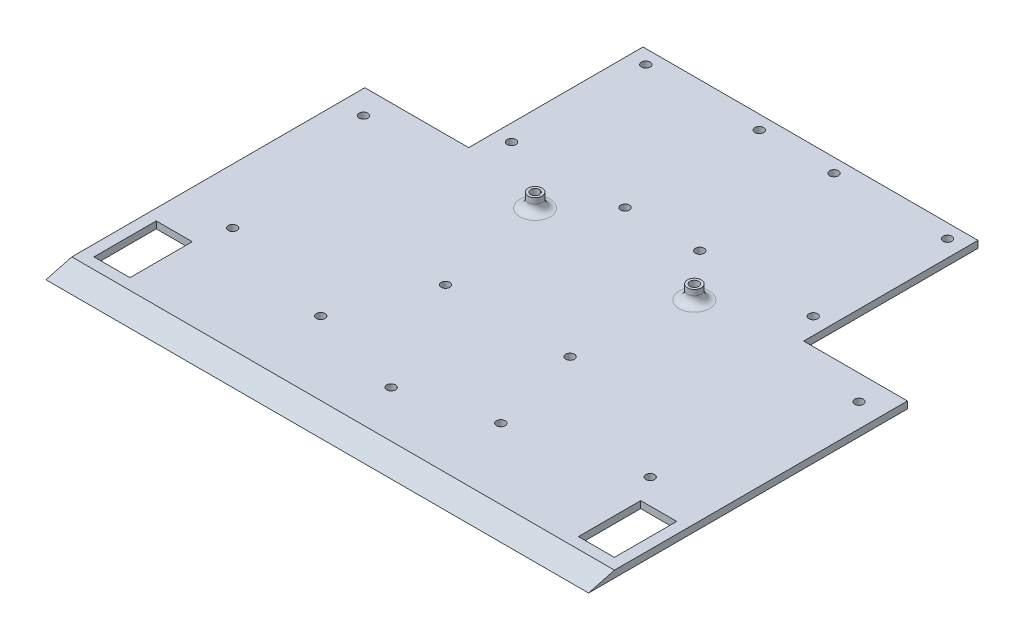
SolidWorks part; units mm, degrees
ref_plane "Alzado" through (0, 0, 0) normal (0, 0, 1) x (1, 0, 0)
ref_plane "Planta" through (0, 0, 0) normal (0, 1, 0) x (1, 0, 0)
ref_plane "Vista lateral" through (0, 0, 0) normal (1, 0, 0) x (0, 0, -1)
sketch "Croquis1" plane through (0, 0, 0) normal (1, 0, 0) x (0, 0, -1)
  line L0 (0, 0) -> (178.17, 0)
  line L1 (178.17, 0) -> (178.17, 2.5)
  line L2 (178.17, 2.5) -> (9.3301, 2.5)
  line L3 (0, 0) -> (9.3301, 2.5)
  dimension "D1" = 178.17
  dimension "D2" = 2.5
  dimension "D3" = 165
extrude "Saliente-Extruir1" add sketch "Croquis1" along normal blind 196
sketch "Croquis2" plane through (0, 0, 0) normal (0, -1, 0) x (-1, 0, 0)
  line L1 (-37.5, 115.1801) -> (0, 115.1801)
  line L2 (-37.5, 115.1801) -> (-37.5, 178.17)
  line L3 (-37.5, 178.17) -> (0, 178.17)
  line L4 (0, 115.1801) -> (0, 178.17)
  line L5 (-37.5, 115.1801) -> (0, 178.17) construction
  line L6 (-37.5, 178.17) -> (0, 115.1801) construction
  line L7 (-158.5, 115.1801) -> (-196, 115.1801)
  line L8 (-158.5, 115.1801) -> (-158.5, 178.17)
  line L9 (-158.5, 178.17) -> (-196, 178.17)
  line L10 (-196, 115.1801) -> (-196, 178.17)
  line L11 (-158.5, 115.1801) -> (-196, 178.17) construction
  line L12 (-158.5, 178.17) -> (-196, 115.1801) construction
  point P4 (-18.75, 146.6751)
  point P11 (-177.25, 146.6751)
extrude "Cortar-Extruir1" cut sketch "Croquis2" against normal up to next
sketch "Croquis4" plane through (0, 2.5, 0) normal (0, 1, 0) x (1, 0, 0)
  line L7 (4, 13.3301) -> (17, 13.3301)
  line L8 (4, 13.3301) -> (4, 35.8301)
  line L9 (4, 35.8301) -> (17, 35.8301)
  line L10 (17, 13.3301) -> (17, 35.8301)
  line L11 (4, 13.3301) -> (17, 35.8301) construction
  line L12 (4, 35.8301) -> (17, 13.3301) construction
  point P9 (10.5, 24.5801)
  dimension "D3" = 22.5
  dimension "D4" = 13
extrude "Cortar-Extruir2" cut sketch "Croquis4" against normal up to next
ref_plane "Plano1" through (98, 0, 0) normal (1, 0, 0) x (0, 0, -1)
mirror "Simetría1" about plane through (98, 0, 0) normal (1, 0, 0) of "Cortar-Extruir2"
sketch "Sketch1" plane through (0, 2.5, 0) normal (0, 1, 0) x (1, 0, 0)
  circle A0 centre (187.5, 106.1801) radius 1.585
  circle A1 centre (8.5, 106.1801) radius 1.585
extrude "Cut-Extrude1" cut sketch "Sketch1" against normal up to next
sketch "Sketch2" plane through (0, 2.5, 0) normal (0, 1, 0) x (1, 0, 0)
  circle A0 centre (98.5, 26.1801) radius 1.585
extrude "Cut-Extrude2" cut sketch "Sketch2" against normal up to next
sketch "Sketch3" plane through (0, 2.5, 0) normal (0, 1, 0) x (1, 0, 0)
  circle A0 centre (111.5, 124.67) radius 1.585
  circle A1 centre (152.5, 124.67) radius 1.585
  circle A2 centre (152.5, 173.17) radius 1.585
  circle A3 centre (111.5, 173.17) radius 1.585
  circle A4 centre (84.5, 173.17) radius 1.585
  circle A5 centre (43.5, 173.17) radius 1.585
  circle A6 centre (43.5, 124.67) radius 1.585
  circle A7 centre (84.5, 124.67) radius 1.585
extrude "Cut-Extrude3" cut sketch "Sketch3" against normal up to next
sketch "Sketch4" plane through (0, 2.5, 0) normal (0, 1, 0) x (1, 0, 0)
  circle A0 centre (125.8764, 108.3369) radius 1.6
  circle A1 centre (68.4153, 108.2804) radius 1.6
  circle A2 centre (68.4153, 108.2804) radius 2.5
  circle A3 centre (125.8764, 108.3369) radius 2.5
  dimension "D1" = 5
  dimension "D2" = 5
extrude "Boss-Extrude1" add sketch "Sketch4" along normal blind 5
sketch "Sketch8" plane through (0, 2.5, 0) normal (0, 1, 0) x (1, 0, 0)
  circle A0 centre (68.4153, 108.2804) radius 1.6
  circle A1 centre (125.8764, 108.3369) radius 1.6
extrude "Cut-Extrude6" cut sketch "Sketch8" against normal through all
fillet "Fillet1" radius 3 2 edges at (68.4153, 2.5, -110.7804) (125.8764, 2.5, -110.8369)
sketch "Sketch12" plane through (0, 2.5, 0) normal (0, 1, 0) x (1, 0, 0)
  circle A0 centre (20.0108, 47.4177) radius 1.5754
  circle A1 centre (63.4681, 35.7734) radius 1.5754
  circle A4 centre (129.5237, 34.7796) radius 1.5754
  circle A5 centre (173.3608, 44.9002) radius 1.5754
extrude "Cut-Extrude9" cut sketch "Sketch12" against normal blind 10
sketch "Sketch13" plane through (0, 2.5, 0) normal (0, 1, 0) x (1, 0, 0)
  circle A0 centre (79.2653, 67.3419) radius 1.5754
  circle A1 centre (124.2555, 67.3419) radius 1.5754
sketch "Sketch14" plane through (0, 2.5, 0) normal (0, 1, 0) x (1, 0, 0)
  circle A0 centre (76.2423, 68.0957) radius 1.5754
  circle A1 centre (121.2325, 68.0957) radius 1.5754
extrude "Cut-Extrude10" cut sketch "Sketch14" against normal blind 10
